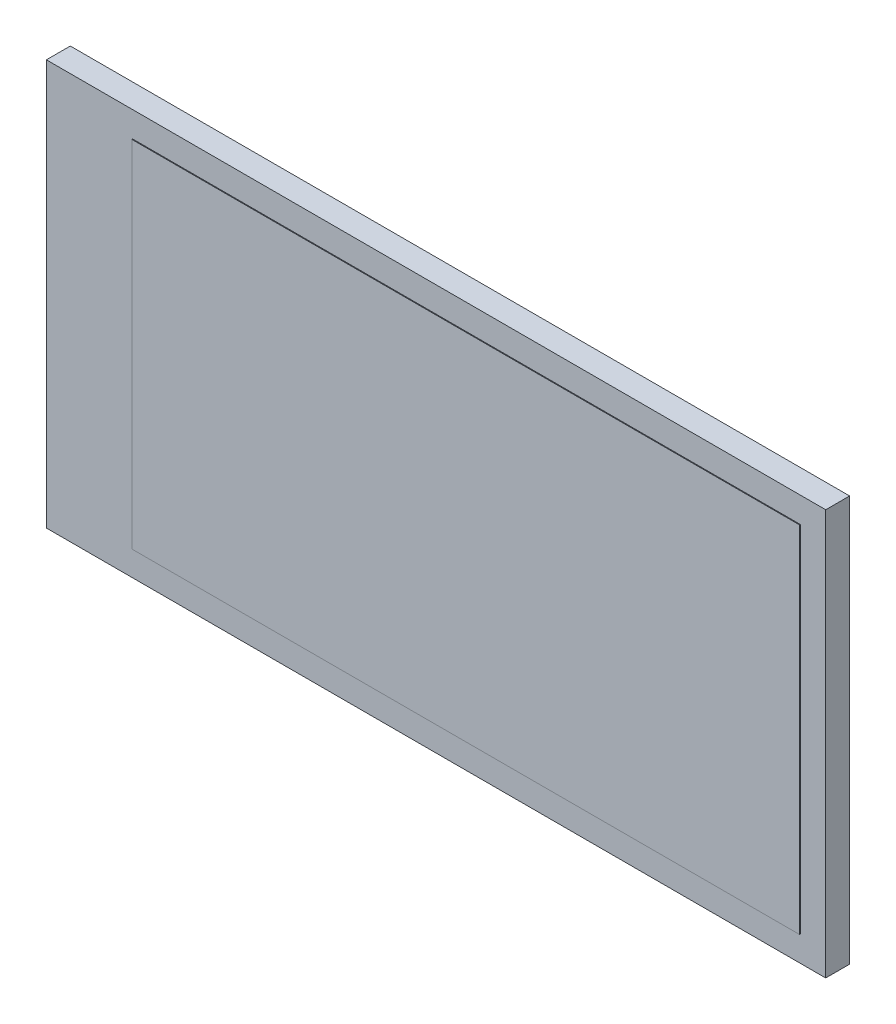
SolidWorks part; units mm, degrees
material "Plastique personnalisé"
ref_plane "Plan de face" through (0, 0, 0) normal (0, 0, 1) x (1, 0, 0)
ref_plane "Plan de dessus" through (0, 0, 0) normal (0, 1, 0) x (1, 0, 0)
ref_plane "Plan de droite" through (0, 0, 0) normal (1, 0, 0) x (0, 0, -1)
sketch "Esquisse1" plane through (0, 0, 0) normal (0, 0, 1) x (1, 0, 0)
  line L1 (-24.935, -12.975) -> (24.935, -12.975)
  line L2 (-24.935, -12.975) -> (-24.935, 12.975)
  line L3 (-24.935, 12.975) -> (24.935, 12.975)
  line L4 (24.935, -12.975) -> (24.935, 12.975)
  line L5 (-24.935, -12.975) -> (24.935, 12.975) construction
  line L6 (-24.935, 12.975) -> (24.935, -12.975) construction
  point P0 (0, 0)
  dimension "D1" = 49.87
  dimension "D2" = 25.95
extrude "Boss.-Extru.1" add sketch "Esquisse1" along normal blind 1.53
sketch "Esquisse2" plane through (0, 0, 1.53) normal (0, 0, 1) x (1, 0, 0)
  line L0 (-24.935, 12.975) -> (-24.935, 11.3481) construction
  line L1 (-24.935, 12.975) -> (-24.935, -12.975) construction
  line L2 (-24.935, 11.3481) -> (-19.4131, 11.3481) construction
  line L4 (-19.4131, 11.3481) -> (23.3069, 11.3481)
  line L5 (-19.4131, 11.3481) -> (-19.4131, -11.3519)
  line L6 (-19.4131, -11.3519) -> (23.3069, -11.3519)
  line L7 (23.3069, 11.3481) -> (23.3069, -11.3519)
  dimension "D1" = 42.72
  dimension "D2" = 22.7
extrude "Boss.-Extru.2" add sketch "Esquisse2" along normal blind 0.05
